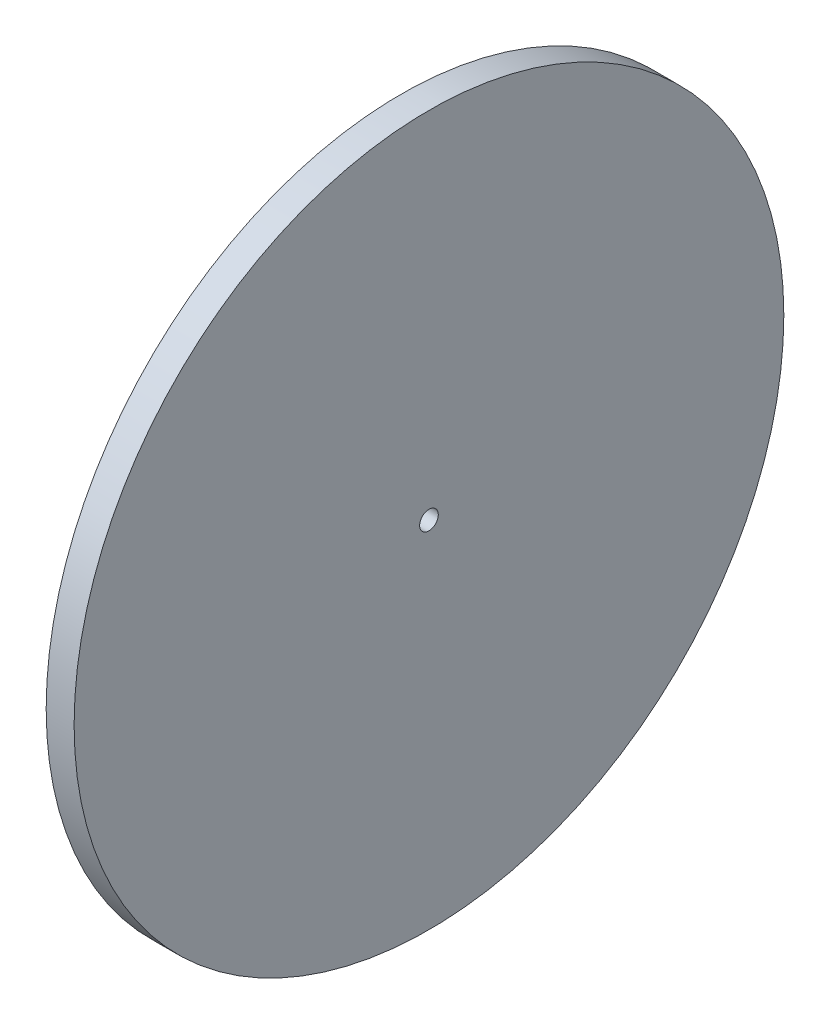
SolidWorks part; units mm, degrees
ref_plane "Front Plane" through (0, 0, 0) normal (0, 0, 1) x (1, 0, 0)
ref_plane "Top Plane" through (0, 0, 0) normal (0, 1, 0) x (1, 0, 0)
ref_plane "Right Plane" through (0, 0, 0) normal (1, 0, 0) x (0, 0, -1)
sketch "Sketch1" plane through (0, 0, 0) normal (0, 0, 1) x (1, 0, 0)
  line L0 (0, 0) -> (3.0794, 0) construction
  line L1 (0, 2) -> (3, 2)
  line L2 (0, 2) -> (0, 57)
  line L3 (-1.5364, 76.2) -> (3, 76.2)
  line L4 (3, 2) -> (3, 76.2)
  line L5 (-1.5364, 76.2) -> (-3, 76.2)
  line L8 (-3, 76.2) -> (-3, 62)
  line L9 (-5, 60) -> (-12, 60)
  line L11 (0, 57) -> (-12, 57)
  line L12 (-12, 60) -> (-12, 57)
  line L13 (0, 2) -> (0, 0) construction
  arc A0 (-5, 60) -> (-3, 62) centre (-5, 62) ccw
  dimension "D8" = 2
  dimension "D1" = 2
  dimension "D2" = 76.2
  dimension "D3" = 3
  dimension "D4" = 6
  dimension "D5" = 57
  dimension "D6" = 3
  dimension "D7" = 12
revolve "Revolve1" add sketch "Sketch1" angle 360 about L0
